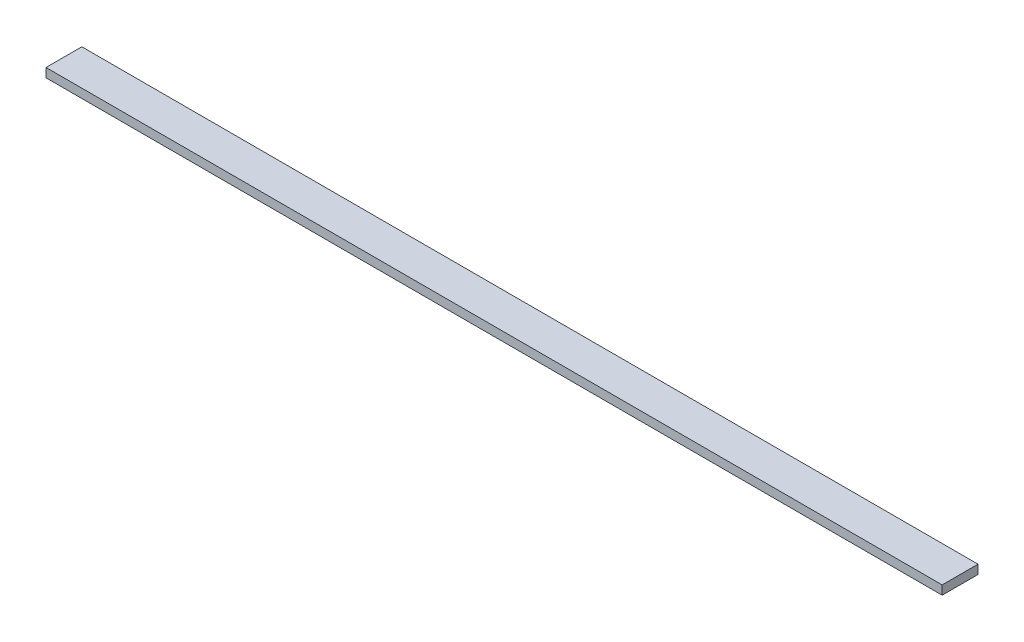
SolidWorks part; units mm, degrees
ref_plane "Front Plane" through (0, 0, 0) normal (0, 0, 1) x (1, 0, 0)
ref_plane "Top Plane" through (0, 0, 0) normal (0, 1, 0) x (1, 0, 0)
ref_plane "Right Plane" through (0, 0, 0) normal (1, 0, 0) x (0, 0, -1)
sketch "Sketch1" plane through (0, 0, 0) normal (0, 1, 0) x (1, 0, 0)
  line L1 (-250, 10) -> (250, 10)
  line L2 (-250, 10) -> (-250, -10)
  line L3 (-250, -10) -> (250, -10)
  line L4 (250, 10) -> (250, -10)
  line L5 (-250, 10) -> (250, -10) construction
  line L6 (-250, -10) -> (250, 10) construction
  point P0 (0, 0)
extrude "Boss-Extrude1" add sketch "Sketch1" along normal blind 5
